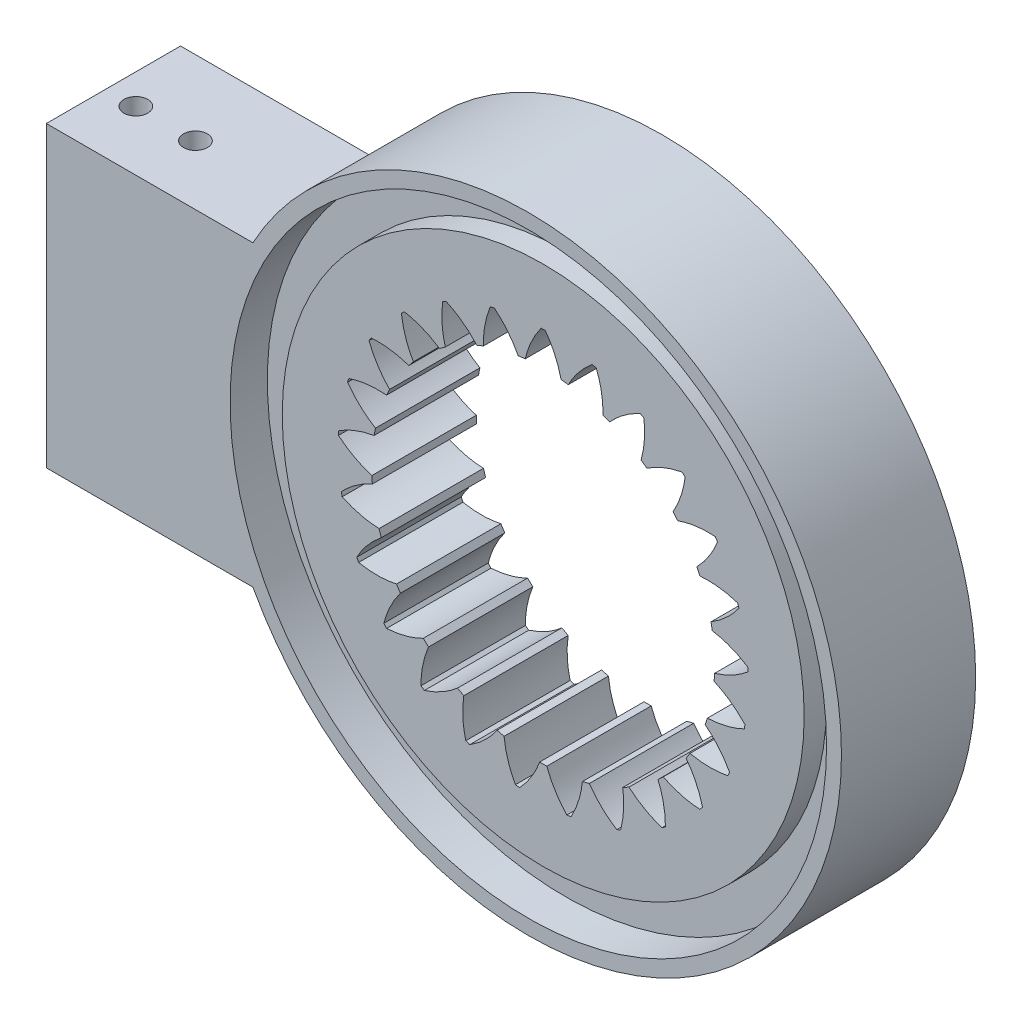
SolidWorks part; units mm, degrees
ref_plane "前视基准面" through (0, 0, 0) normal (0, 0, 1) x (1, 0, 0)
ref_plane "上视基准面" through (0, 0, 0) normal (0, 1, 0) x (1, 0, 0)
ref_plane "右视基准面" through (0, 0, 0) normal (1, 0, 0) x (0, 0, -1)
sketch "草图1" plane through (0, 0, 0) normal (0, 0, 1) x (1, 0, 0)
  line L0 (0, 0) -> (0, 40)
  line L1 (0, 40) -> (27.7086, 40)
  line L2 (0, 0) -> (27.7086, 0)
  arc A1 (27.7086, 0) -> (27.7086, 40) centre (64.641, 20) ccw
extrude "凸台-拉伸1" add sketch "草图1" along normal blind 18
sketch "草图2" plane through (0, 0, 0) normal (0, 0, 1) x (1, 0, 0)
  circle A1 centre (64.641, 20) radius 35
  circle A2 centre (64.641, 20) radius 40
extrude "切除-拉伸1" cut sketch "草图2" along normal blind 5
sketch "草图3" plane through (0, 0, 0) normal (0, 0, 1) x (1, 0, 0)
  circle A0 centre (64.641, 20) radius 37.5
extrude "切除-拉伸2" cut sketch "草图3" along normal blind 2
sketch "草图4" plane through (0, 0, 0) normal (0, 0, 1) x (1, 0, 0)
  circle A0 centre (64.641, 20) radius 20
extrude "切除-拉伸3" cut sketch "草图4" along normal blind 20
ref_plane "基准面1" through (0, 0, 18) normal (0, 0, 1) x (1, 0, 0)
sketch "草图5" plane through (0, 0, 18) normal (0, 0, 1) x (1, 0, 0)
  circle A0 centre (64.641, 20) radius 40
  circle A1 centre (64.641, 20) radius 35
extrude "切除-拉伸4" cut sketch "草图5" against normal blind 5
sketch "草图6" plane through (0, 0, 18) normal (0, 0, 1) x (1, 0, 0)
  circle A0 centre (64.641, 20) radius 37.5
extrude "切除-拉伸5" cut sketch "草图6" against normal blind 2
sketch "草图7" plane through (0, 0, 0) normal (0, 1, 0) x (1, 0, 0)
  circle A0 centre (4, -10) radius 1.6
  circle A1 centre (12, -10) radius 1.6
extrude "切除-拉伸6" cut sketch "草图7" along normal blind 60
sketch "草图8" plane through (0, 0, 0) normal (0, 0, 1) x (1, 0, 0)
  line L0 (62.2359, 42.783) -> (61.2821, 42.6625)
  line L1 (64.3619, 47.4087) -> (64.9201, 47.4087)
  line L2 (68, 42.6625) -> (67.0461, 42.783)
  line L3 (71.2096, 46.6141) -> (71.7502, 46.4753)
  line L4 (73.553, 41.1123) -> (72.6591, 41.4662)
  line L5 (77.6445, 44.1416) -> (78.1336, 43.8727)
  line L6 (78.546, 38.2298) -> (77.7682, 38.795)
  line L7 (83.2623, 40.1464) -> (83.6692, 39.7644)
  line L8 (82.6654, 34.1962) -> (82.0525, 34.937)
  line L9 (87.7101, 34.8797) -> (88.0092, 34.4085)
  line L10 (85.6522, 29.2649) -> (85.2428, 30.1348)
  line L11 (90.7084, 28.6723) -> (90.8809, 28.1415)
  line L12 (87.3188, 23.7457) -> (87.1386, 24.6901)
  line L13 (92.0688, 21.9143) -> (92.1039, 21.3573)
  line L14 (87.5604, 17.9854) -> (87.6208, 18.945)
  line L15 (91.7058, 15.0303) -> (91.6012, 14.482)
  line L16 (86.362, 12.346) -> (86.6591, 13.2604)
  line L17 (89.6422, 8.4528) -> (89.4046, 7.9478)
  line L18 (83.7987, 7.1819) -> (84.3139, 7.9936)
  line L19 (86.0077, 2.5952) -> (85.6519, 2.1651)
  line L20 (80.0317, 2.8174) -> (80.7326, 3.4755)
  line L21 (81.0306, -2.1745) -> (80.5791, -2.5026)
  line L22 (75.2977, -0.4732) -> (76.1402, -0.01)
  line L23 (75.0238, -5.5567) -> (74.5048, -5.7621)
  line L24 (69.894, -2.483) -> (70.8253, -2.2439)
  line L25 (68.3645, -7.3387) -> (67.8108, -7.4087)
  line L26 (64.1603, -3.0859) -> (65.1217, -3.0859)
  line L27 (61.4713, -7.4087) -> (60.9175, -7.3387)
  line L28 (58.4568, -2.2439) -> (59.388, -2.483)
  line L29 (54.7772, -5.7621) -> (54.2583, -5.5567)
  line L30 (53.1418, -0.01) -> (53.9844, -0.4732)
  line L31 (48.7029, -2.5026) -> (48.2514, -2.1745)
  line L32 (48.5494, 3.4755) -> (49.2503, 2.8174)
  line L33 (43.6301, 2.1651) -> (43.2743, 2.5952)
  line L34 (44.9681, 7.9936) -> (45.4833, 7.1819)
  line L35 (39.8775, 7.9478) -> (39.6398, 8.4528)
  line L36 (42.6229, 13.2604) -> (42.92, 12.346)
  line L37 (37.6808, 14.482) -> (37.5762, 15.0303)
  line L38 (41.6612, 18.945) -> (41.7216, 17.9854)
  line L39 (37.1782, 21.3573) -> (37.2132, 21.9143)
  line L40 (42.1434, 24.6901) -> (41.9633, 23.7457)
  line L41 (38.4011, 28.1415) -> (38.5736, 28.6723)
  line L42 (44.0392, 30.1348) -> (43.6299, 29.2649)
  line L43 (41.2728, 34.4085) -> (41.5719, 34.8797)
  line L44 (47.2295, 34.937) -> (46.6167, 34.1962)
  line L45 (45.6128, 39.7644) -> (46.0197, 40.1464)
  line L46 (51.5138, 38.795) -> (50.736, 38.2298)
  line L47 (51.1484, 43.8727) -> (51.6375, 44.1416)
  line L48 (56.623, 41.4662) -> (55.729, 41.1123)
  line L49 (57.5318, 46.4753) -> (58.0725, 46.6141)
  spline S0 degree 2 poles (62.2359, 42.783) (62.823, 45.3146) (64.3619, 47.4087) knots 0 0 0 1 1 1
  spline S1 degree 2 poles (61.2821, 42.6625) (60.0839, 44.9685) (58.0725, 46.6141) knots 0 0 0 1 1 1
  spline S2 degree 2 poles (68, 42.6625) (69.1982, 44.9685) (71.2096, 46.6141) knots 0 0 0 1 1 1
  spline S3 degree 2 poles (67.0461, 42.783) (66.4591, 45.3146) (64.9201, 47.4087) knots 0 0 0 1 1 1
  spline S4 degree 2 poles (73.553, 41.1123) (75.287, 43.0479) (77.6445, 44.1416) knots 0 0 0 1 1 1
  spline S5 degree 2 poles (72.6591, 41.4662) (72.72, 44.0643) (71.7502, 46.4753) knots 0 0 0 1 1 1
  spline S6 degree 2 poles (78.546, 38.2298) (80.707, 39.6734) (83.2623, 40.1464) knots 0 0 0 1 1 1
  spline S7 degree 2 poles (77.7682, 38.795) (78.4734, 41.2962) (78.1336, 43.8727) knots 0 0 0 1 1 1
  spline S8 degree 2 poles (82.6654, 34.1962) (85.1174, 35.057) (87.7101, 34.8797) knots 0 0 0 1 1 1
  spline S9 degree 2 poles (82.0525, 34.937) (83.3576, 37.1843) (83.6692, 39.7644) knots 0 0 0 1 1 1
  spline S10 degree 2 poles (85.6522, 29.2649) (88.2413, 29.4889) (90.7084, 28.6723) knots 0 0 0 1 1 1
  spline S11 degree 2 poles (85.2428, 30.1348) (87.0658, 31.987) (88.0092, 34.4085) knots 0 0 0 1 1 1
  spline S12 degree 2 poles (87.3188, 23.7457) (89.8822, 23.3188) (92.0688, 21.9143) knots 0 0 0 1 1 1
  spline S13 degree 2 poles (87.1386, 24.6901) (89.3649, 26.0307) (90.8809, 28.1415) knots 0 0 0 1 1 1
  spline S14 degree 2 poles (87.5604, 17.9854) (89.9372, 16.9344) (91.7058, 15.0303) knots 0 0 0 1 1 1
  spline S15 degree 2 poles (87.6208, 18.945) (90.1105, 19.6898) (92.1039, 21.3573) knots 0 0 0 1 1 1
  spline S16 degree 2 poles (86.362, 12.346) (88.4027, 10.737) (89.6422, 8.4528) knots 0 0 0 1 1 1
  spline S17 degree 2 poles (86.6591, 13.2604) (89.2558, 13.3627) (91.6012, 14.482) knots 0 0 0 1 1 1
  spline S18 degree 2 poles (83.7987, 7.1819) (85.3752, 5.1158) (86.0077, 2.5952) knots 0 0 0 1 1 1
  spline S19 degree 2 poles (84.3139, 7.9936) (86.8545, 7.4469) (89.4046, 7.9478) knots 0 0 0 1 1 1
  spline S20 degree 2 poles (80.0317, 2.8174) (81.0448, 0.4242) (81.0306, -2.1745) knots 0 0 0 1 1 1
  spline S21 degree 2 poles (80.7326, 3.4755) (83.0574, 2.3142) (85.6519, 2.1651) knots 0 0 0 1 1 1
  spline S22 degree 2 poles (75.2977, -0.4732) (75.6838, -3.0431) (75.0238, -5.5567) knots 0 0 0 1 1 1
  spline S23 degree 2 poles (76.1402, -0.01) (78.1032, -1.713) (80.5791, -2.5026) knots 0 0 0 1 1 1
  spline S24 degree 2 poles (69.894, -2.483) (69.6289, -5.0682) (68.3645, -7.3387) knots 0 0 0 1 1 1
  spline S25 degree 2 poles (70.8253, -2.2439) (72.303, -4.3816) (74.5048, -5.7621) knots 0 0 0 1 1 1
  spline S26 degree 2 poles (64.1603, -3.0859) (63.2606, -5.524) (61.4713, -7.4087) knots 0 0 0 1 1 1
  spline S27 degree 2 poles (65.1217, -3.0859) (66.0215, -5.524) (67.8108, -7.4087) knots 0 0 0 1 1 1
  spline S28 degree 2 poles (58.4568, -2.2439) (56.979, -4.3816) (54.7772, -5.7621) knots 0 0 0 1 1 1
  spline S29 degree 2 poles (59.388, -2.483) (59.6531, -5.0682) (60.9175, -7.3387) knots 0 0 0 1 1 1
  spline S30 degree 2 poles (53.1418, -0.01) (51.1789, -1.713) (48.7029, -2.5026) knots 0 0 0 1 1 1
  spline S31 degree 2 poles (53.9844, -0.4732) (53.5982, -3.0431) (54.2583, -5.5567) knots 0 0 0 1 1 1
  spline S32 degree 2 poles (48.5494, 3.4755) (46.2246, 2.3142) (43.6301, 2.1651) knots 0 0 0 1 1 1
  spline S33 degree 2 poles (49.2503, 2.8174) (48.2372, 0.4242) (48.2514, -2.1745) knots 0 0 0 1 1 1
  spline S34 degree 2 poles (44.9681, 7.9936) (42.4275, 7.4469) (39.8775, 7.9478) knots 0 0 0 1 1 1
  spline S35 degree 2 poles (45.4833, 7.1819) (43.9069, 5.1158) (43.2743, 2.5952) knots 0 0 0 1 1 1
  spline S36 degree 2 poles (42.6229, 13.2604) (40.0262, 13.3627) (37.6808, 14.482) knots 0 0 0 1 1 1
  spline S37 degree 2 poles (42.92, 12.346) (40.8793, 10.737) (39.6398, 8.4528) knots 0 0 0 1 1 1
  spline S38 degree 2 poles (41.6612, 18.945) (39.1715, 19.6898) (37.1782, 21.3573) knots 0 0 0 1 1 1
  spline S39 degree 2 poles (41.7216, 17.9854) (39.3448, 16.9344) (37.5762, 15.0303) knots 0 0 0 1 1 1
  spline S40 degree 2 poles (42.1434, 24.6901) (39.9171, 26.0307) (38.4011, 28.1415) knots 0 0 0 1 1 1
  spline S41 degree 2 poles (41.9633, 23.7457) (39.3998, 23.3188) (37.2132, 21.9143) knots 0 0 0 1 1 1
  spline S42 degree 2 poles (44.0392, 30.1348) (42.2163, 31.987) (41.2728, 34.4085) knots 0 0 0 1 1 1
  spline S43 degree 2 poles (43.6299, 29.2649) (41.0408, 29.4889) (38.5736, 28.6723) knots 0 0 0 1 1 1
  spline S44 degree 2 poles (47.2295, 34.937) (45.9245, 37.1843) (45.6128, 39.7644) knots 0 0 0 1 1 1
  spline S45 degree 2 poles (46.6167, 34.1962) (44.1646, 35.057) (41.5719, 34.8797) knots 0 0 0 1 1 1
  spline S46 degree 2 poles (51.5138, 38.795) (50.8087, 41.2962) (51.1484, 43.8727) knots 0 0 0 1 1 1
  spline S47 degree 2 poles (50.736, 38.2298) (48.5751, 39.6734) (46.0197, 40.1464) knots 0 0 0 1 1 1
  spline S48 degree 2 poles (56.623, 41.4662) (56.562, 44.0643) (57.5318, 46.4753) knots 0 0 0 1 1 1
  spline S49 degree 2 poles (55.729, 41.1123) (53.995, 43.0479) (51.6375, 44.1416) knots 0 0 0 1 1 1
extrude "切除-拉伸7" cut sketch "草图8" along normal blind 20
sketch "草图9" plane through (0, 0, 0) normal (0, 0, 1) x (1, 0, 0)
  line L0 (64.641, 20) -> (64.641, 47.4087)
  line L1 (64.3619, 47.4087) -> (64.9201, 47.4087) construction
ref_plane "基准面2" through (64.641, 0, 0) normal (1, 0, 0) x (0, 0, -1)
sketch "草图10" plane through (64.641, 0, 0) normal (1, 0, 0) x (0, 0, -1)
  line L0 (0, 20) -> (-18, 20)
  line L1 (0, 20) -> (0, 47.4087) construction
  line L2 (-18, 62) -> (-18, -22) construction
